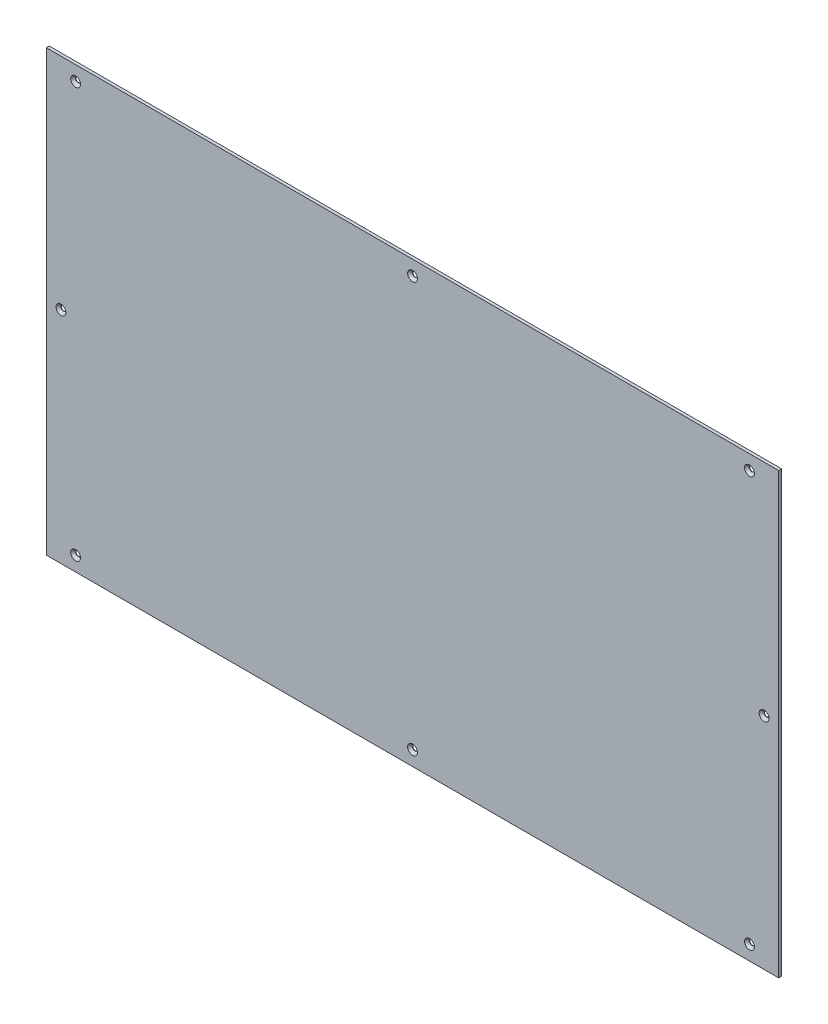
SolidWorks part; units mm, degrees
ref_plane "Front Plane" through (0, 0, 0) normal (0, 0, 1) x (1, 0, 0)
ref_plane "Top Plane" through (0, 0, 0) normal (0, 1, 0) x (1, 0, 0)
ref_plane "Right Plane" through (0, 0, 0) normal (1, 0, 0) x (0, 0, -1)
sketch "Sketch1" plane through (0, 0, 0) normal (0, 0, 1) x (1, 0, 0)
  line L1 (-500, -300) -> (500, -300)
  line L2 (-500, -300) -> (-500, 300)
  line L3 (-500, 300) -> (500, 300)
  line L4 (500, -300) -> (500, 300)
  line L5 (-500, -300) -> (500, 300) construction
  line L6 (-500, 300) -> (500, -300) construction
  point P0 (0, 0)
  dimension "D1" = 1000
  dimension "D2" = 600
extrude "Boss-Extrude1" add sketch "Sketch1" along normal blind 4
sketch "Sketch2" plane through (0, 0, 4) normal (0, 0, 1) x (1, 0, 0)
  line L0 (-480, 378.3904) -> (-480, -313.5535) construction
  line L17 (-435.4748, 280) -> (450.358, 280) construction
  line L18 (-427.4037, -280) -> (432.8239, -280) construction
  line L19 (-500, 300) -> (-500, -300) construction
  line L20 (-500, -300) -> (500, -300) construction
  line L21 (500, 300) -> (-500, 300) construction
  line L22 (500, -300) -> (500, 300) construction
  line L23 (480, 365.8937) -> (480, -292.0763) construction
  point P32 (-460, -280)
  point P33 (460, -280)
  point P34 (-460, 280)
  point P35 (460, 280)
  point P36 (-480, 0)
  point P37 (480, 0)
  point P38 (0, 280)
  point P39 (0, -280)
  dimension "D2" = 40
  dimension "D3" = 40
  dimension "D4" = 40
  dimension "D5" = 40
  dimension "D6" = 300
  dimension "D7" = 20
  dimension "D8" = 300
  dimension "D9" = 20
  dimension "D10" = 20
  dimension "D11" = 20
  dimension "D18" = 0
  dimension "D19" = 0
hole_wizard "CSK for M6 Hex Socket Countersunk Cap Screw1" positions "Sketch3" profile "Sketch4" countersink size "M6" standard "ISO" end condition through all
sketch "Sketch3" plane through (0, 0, 4) normal (0, 0, 1) x (1, 0, 0)
  point P0 (-480, 0)
  point P3 (480, 0)
  point P6 (-460, -280)
  point P9 (0, -280)
  point P12 (460, -280)
  point P15 (460, 280)
  point P18 (0, 280)
  point P21 (-460, 280)
sketch "Sketch4" plane through (-480, 0, 4) normal (1, 0, 0) x (0, -1, 0)
  line L0 (0, 0) -> (0, 4)
  line L1 (0, 4) -> (3.3, 4)
  line L2 (3.3, 4) -> (3.3, 3.42)
  line L3 (3.3, 3.42) -> (6.72, 0)
  line L5 (6.72, 0) -> (0, 0)
  line L6 (-3.3, 3.42) -> (-6.72, 0) construction
  line L11 (0, -6.35) -> (0, 107.95) construction
  dimension "Thru Hole Dia." = 6.6
  dimension "Thru Hole Depth" = 4
  dimension "Near C'Sink Dia." = 13.44
  dimension "Near C'Sink Angle" = 90
